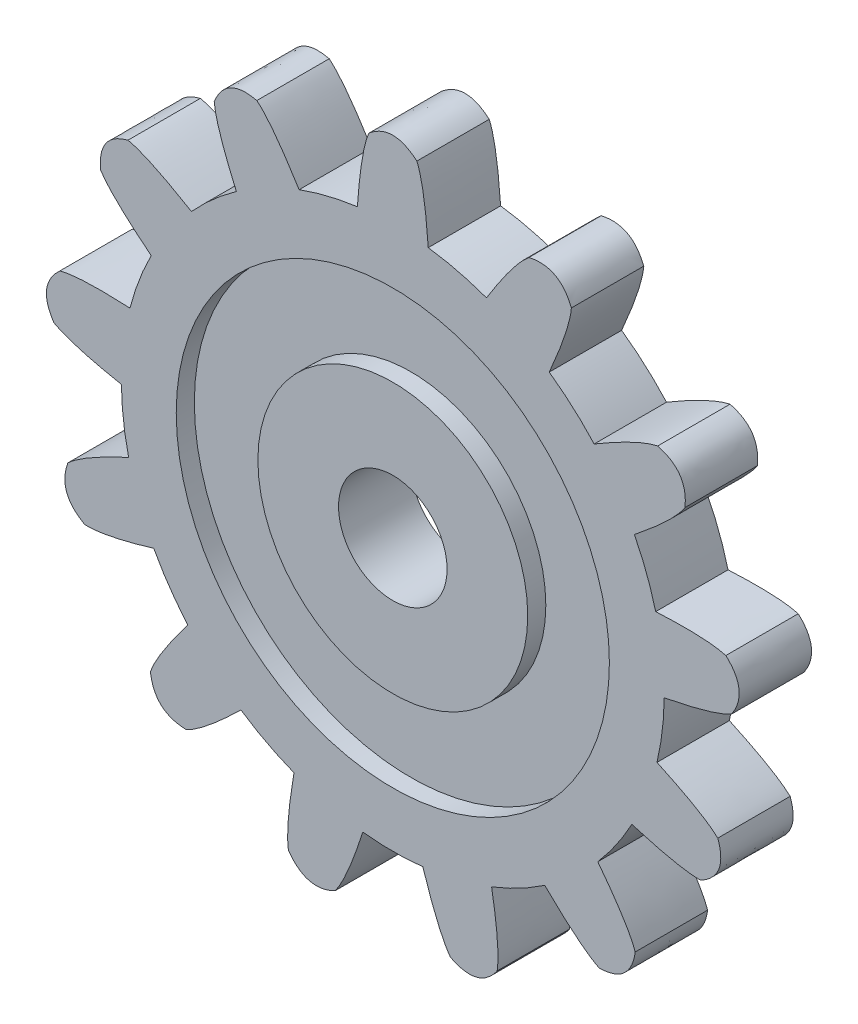
SolidWorks part; units mm, degrees
ref_plane "Front Plane" through (0, 0, 0) normal (0, 0, 1) x (1, 0, 0)
ref_plane "Top Plane" through (0, 0, 0) normal (0, 1, 0) x (1, 0, 0)
ref_plane "Right Plane" through (0, 0, 0) normal (1, 0, 0) x (0, 0, -1)
sketch "Sketch1" plane through (0, 0, 0) normal (0, 0, 1) x (1, 0, 0)
  line L0 (0, 39.9061) -> (0, 47.5043) construction
  line L1 (-3.3789, 47.5043) -> (3.3789, 47.5043) construction
  line L2 (-3.3789, 47.5043) -> (0, 50.4032) construction
  line L3 (0, 50.4032) -> (3.3789, 47.5043) construction
  line L4 (-4.4671, 44.9352) -> (4.4671, 44.9352) construction
  line L5 (4.4671, 44.9352) -> (4.4671, 44.9672) construction
  line L6 (-3.3789, 47.5043) -> (-4.4671, 44.9352) construction
  line L7 (-4.4671, 44.9352) -> (-4.973, 37.774) construction
  line L8 (0, 47.5043) -> (0, 48.9537) construction
  line L9 (-4.973, 37.774) -> (0, 0) construction
  line L10 (0, 0) -> (0, 39.9061) construction
  line L11 (3.3789, 47.5043) -> (4.4671, 44.9352) construction
  line L12 (4.4671, 44.9352) -> (4.973, 37.774) construction
  line L13 (19.0845, 43.6332) -> (23.4235, 44.6298) construction
  line L14 (23.4235, 44.6298) -> (25.0682, 40.4927) construction
  line L15 (19.0845, 43.6332) -> (16.927, 41.8641) construction
  line L16 (16.927, 41.8641) -> (13.1511, 35.7584) construction
  line L17 (25.0682, 40.4927) -> (24.8379, 37.7122) construction
  line L18 (24.8379, 37.7122) -> (21.9579, 31.1362) construction
  line L19 (37.1758, 29.7663) -> (41.481, 28.6323) construction
  line L20 (41.481, 28.6323) -> (41.0147, 24.2047) construction
  line L21 (37.1758, 29.7663) -> (34.4433, 29.2025) construction
  line L22 (34.4433, 29.2025) -> (28.2624, 25.5508) construction
  line L23 (41.0147, 24.2047) -> (39.5186, 21.8497) construction
  line L24 (39.5186, 21.8497) -> (33.9124, 17.3654) construction
  line L25 (46.7506, 9.0803) -> (50.0357, 6.0754) construction
  line L26 (50.0357, 6.0754) -> (47.5652, 2.3718) construction
  line L27 (46.7506, 9.0803) -> (44.0691, 9.8509) construction
  line L28 (44.0691, 9.8509) -> (36.8992, 9.4899) construction
  line L29 (47.5652, 2.3718) -> (45.146, 0.9818) construction
  line L30 (45.146, 0.9818) -> (38.0981, -0.3836) construction
  line L31 (45.6154, -13.6859) -> (47.1278, -17.8732) construction
  line L32 (47.1278, -17.8732) -> (43.2191, -20.0046) construction
  line L33 (45.6154, -13.6859) -> (43.5992, -11.7574) construction
  line L34 (43.5992, -11.7574) -> (37.0828, -8.745) construction
  line L35 (43.2191, -20.0046) -> (40.4311, -20.1111) construction
  line L36 (40.4311, -20.1111) -> (33.5559, -18.0447) construction
  line L37 (34.0303, -33.3168) -> (33.4235, -37.7273) construction
  line L38 (33.4235, -37.7273) -> (28.972, -37.7981) construction
  line L39 (34.0303, -33.3168) -> (33.1413, -30.6722) construction
  line L40 (33.1413, -30.6722) -> (28.7712, -24.9765) construction
  line L41 (28.972, -37.7981) -> (26.4539, -36.5967) construction
  line L42 (26.4539, -36.5967) -> (21.3264, -31.572) construction
  line L43 (14.6492, -45.3153) -> (12.0623, -48.9386) construction
  line L44 (12.0623, -48.9386) -> (8.0878, -46.9325) construction
  line L45 (14.6492, -45.3153) -> (15.091, -42.5604) construction
  line L46 (15.091, -42.5604) -> (13.8685, -35.4863) construction
  line L47 (8.0878, -46.9325) -> (6.4164, -44.6985) construction
  line L48 (6.4164, -44.6985) -> (4.2114, -37.8665) construction
  line L49 (-8.0878, -46.9325) -> (-12.0623, -48.9386) construction
  line L50 (-12.0623, -48.9386) -> (-14.6492, -45.3153) construction
  line L51 (-8.0878, -46.9325) -> (-6.4164, -44.6985) construction
  line L52 (-6.4164, -44.6985) -> (-4.2114, -37.8665) construction
  line L53 (-14.6492, -45.3153) -> (-15.091, -42.5604) construction
  line L54 (-15.091, -42.5604) -> (-13.8685, -35.4863) construction
  line L55 (-28.972, -37.7981) -> (-33.4235, -37.7273) construction
  line L56 (-33.4235, -37.7273) -> (-34.0303, -33.3168) construction
  line L57 (-28.972, -37.7981) -> (-26.4539, -36.5967) construction
  line L58 (-26.4539, -36.5967) -> (-21.3264, -31.572) construction
  line L59 (-34.0303, -33.3168) -> (-33.1413, -30.6722) construction
  line L60 (-33.1413, -30.6722) -> (-28.7712, -24.9765) construction
  line L61 (-43.2191, -20.0046) -> (-47.1278, -17.8732) construction
  line L62 (-47.1278, -17.8732) -> (-45.6154, -13.6859) construction
  line L63 (-43.2191, -20.0046) -> (-40.4311, -20.1111) construction
  line L64 (-40.4311, -20.1111) -> (-33.5559, -18.0447) construction
  line L65 (-45.6154, -13.6859) -> (-43.5992, -11.7574) construction
  line L66 (-43.5992, -11.7574) -> (-37.0828, -8.745) construction
  line L67 (-47.5652, 2.3718) -> (-50.0357, 6.0754) construction
  line L68 (-50.0357, 6.0754) -> (-46.7506, 9.0803) construction
  line L69 (-47.5652, 2.3718) -> (-45.146, 0.9818) construction
  line L70 (-45.146, 0.9818) -> (-38.0981, -0.3836) construction
  line L71 (-46.7506, 9.0803) -> (-44.0691, 9.8509) construction
  line L72 (-44.0691, 9.8509) -> (-36.8992, 9.4899) construction
  line L73 (-41.0147, 24.2047) -> (-41.481, 28.6323) construction
  line L74 (-41.481, 28.6323) -> (-37.1758, 29.7663) construction
  line L75 (-41.0147, 24.2047) -> (-39.5186, 21.8497) construction
  line L76 (-39.5186, 21.8497) -> (-33.9124, 17.3654) construction
  line L77 (-37.1758, 29.7663) -> (-34.4433, 29.2025) construction
  line L78 (-34.4433, 29.2025) -> (-28.2624, 25.5508) construction
  line L79 (-25.0682, 40.4927) -> (-23.4235, 44.6298) construction
  line L80 (-23.4235, 44.6298) -> (-19.0845, 43.6332) construction
  line L81 (-25.0682, 40.4927) -> (-24.8379, 37.7122) construction
  line L82 (-24.8379, 37.7122) -> (-21.9579, 31.1362) construction
  line L83 (-19.0845, 43.6332) -> (-16.927, 41.8641) construction
  line L84 (-16.927, 41.8641) -> (-13.1511, 35.7584) construction
  arc A0 (-4.973, 37.774) -> (-13.1511, 35.7584) centre (0, 0) ccw
  circle A1 centre (0, 0) radius 7.62
  arc A2 (-21.9579, 31.1362) -> (-28.2624, 25.5508) centre (0, 0) ccw
  arc A3 (13.1511, 35.7584) -> (4.973, 37.774) centre (0, 0) ccw
  arc A4 (28.2624, 25.5508) -> (21.9579, 31.1362) centre (0, 0) ccw
  arc A5 (36.8992, 9.4899) -> (33.9124, 17.3654) centre (0, 0) ccw
  arc A6 (-33.9124, 17.3654) -> (-36.8992, 9.4899) centre (0, 0) ccw
  arc A7 (-38.0981, -0.3836) -> (-37.0828, -8.745) centre (0, 0) ccw
  arc A8 (-33.5559, -18.0447) -> (-28.7712, -24.9765) centre (0, 0) ccw
  arc A9 (-21.3264, -31.572) -> (-13.8685, -35.4863) centre (0, 0) ccw
  arc A10 (-4.2114, -37.8665) -> (4.2114, -37.8665) centre (0, 0) ccw
  arc A11 (13.8685, -35.4863) -> (21.3264, -31.572) centre (0, 0) ccw
  arc A12 (28.7712, -24.9765) -> (33.5559, -18.0447) centre (0, 0) ccw
  arc A13 (37.0828, -8.745) -> (38.0981, -0.3836) centre (0, 0) ccw
  circle A14 centre (0, 0) radius 38.1 construction
  spline S0 degree 2 poles (-3.3789, 47.5043) (0, 50.4032) (3.3789, 47.5043) knots 0 0 0 1 1 1
  spline S1 degree 2 poles (-3.3789, 47.5043) (-4.4671, 44.9352) (-4.973, 37.774) knots 0 0 0 1 1 1
  spline S2 degree 2 poles (3.3789, 47.5043) (4.4671, 44.9352) (4.973, 37.774) knots 0 0 0 1 1 1
  spline S3 degree 2 poles (19.0845, 43.6332) (16.927, 41.8641) (13.1511, 35.7584) knots 0 0 0 1 1 1
  spline S4 degree 2 poles (19.0845, 43.6332) (23.4235, 44.6298) (25.0682, 40.4927) knots 0 0 0 1 1 1
  spline S5 degree 2 poles (25.0682, 40.4927) (24.8379, 37.7122) (21.9579, 31.1362) knots 0 0 0 1 1 1
  spline S6 degree 2 poles (37.1758, 29.7663) (34.4433, 29.2025) (28.2624, 25.5508) knots 0 0 0 1 1 1
  spline S7 degree 2 poles (37.1758, 29.7663) (41.481, 28.6323) (41.0147, 24.2047) knots 0 0 0 1 1 1
  spline S8 degree 2 poles (41.0147, 24.2047) (39.5186, 21.8497) (33.9124, 17.3654) knots 0 0 0 1 1 1
  spline S9 degree 2 poles (46.7506, 9.0803) (44.0691, 9.8509) (36.8992, 9.4899) knots 0 0 0 1 1 1
  spline S10 degree 2 poles (46.7506, 9.0803) (50.0357, 6.0754) (47.5652, 2.3718) knots 0 0 0 1 1 1
  spline S11 degree 2 poles (47.5652, 2.3718) (45.146, 0.9818) (38.0981, -0.3836) knots 0 0 0 1 1 1
  spline S12 degree 2 poles (45.6154, -13.6859) (43.5992, -11.7574) (37.0828, -8.745) knots 0 0 0 1 1 1
  spline S13 degree 2 poles (45.6154, -13.6859) (47.1278, -17.8732) (43.2191, -20.0046) knots 0 0 0 1 1 1
  spline S14 degree 2 poles (43.2191, -20.0046) (40.4311, -20.1111) (33.5559, -18.0447) knots 0 0 0 1 1 1
  spline S15 degree 2 poles (34.0303, -33.3168) (33.1413, -30.6722) (28.7712, -24.9765) knots 0 0 0 1 1 1
  spline S16 degree 2 poles (34.0303, -33.3168) (33.4235, -37.7273) (28.972, -37.7981) knots 0 0 0 1 1 1
  spline S17 degree 2 poles (28.972, -37.7981) (26.4539, -36.5967) (21.3264, -31.572) knots 0 0 0 1 1 1
  spline S18 degree 2 poles (14.6492, -45.3153) (15.091, -42.5604) (13.8685, -35.4863) knots 0 0 0 1 1 1
  spline S19 degree 2 poles (14.6492, -45.3153) (12.0623, -48.9386) (8.0878, -46.9325) knots 0 0 0 1 1 1
  spline S20 degree 2 poles (8.0878, -46.9325) (6.4164, -44.6985) (4.2114, -37.8665) knots 0 0 0 1 1 1
  spline S21 degree 2 poles (-8.0878, -46.9325) (-6.4164, -44.6985) (-4.2114, -37.8665) knots 0 0 0 1 1 1
  spline S22 degree 2 poles (-8.0878, -46.9325) (-12.0623, -48.9386) (-14.6492, -45.3153) knots 0 0 0 1 1 1
  spline S23 degree 2 poles (-14.6492, -45.3153) (-15.091, -42.5604) (-13.8685, -35.4863) knots 0 0 0 1 1 1
  spline S24 degree 2 poles (-28.972, -37.7981) (-26.4539, -36.5967) (-21.3264, -31.572) knots 0 0 0 1 1 1
  spline S25 degree 2 poles (-28.972, -37.7981) (-33.4235, -37.7273) (-34.0303, -33.3168) knots 0 0 0 1 1 1
  spline S26 degree 2 poles (-34.0303, -33.3168) (-33.1413, -30.6722) (-28.7712, -24.9765) knots 0 0 0 1 1 1
  spline S27 degree 2 poles (-43.2191, -20.0046) (-40.4311, -20.1111) (-33.5559, -18.0447) knots 0 0 0 1 1 1
  spline S28 degree 2 poles (-43.2191, -20.0046) (-47.1278, -17.8732) (-45.6154, -13.6859) knots 0 0 0 1 1 1
  spline S29 degree 2 poles (-45.6154, -13.6859) (-43.5992, -11.7574) (-37.0828, -8.745) knots 0 0 0 1 1 1
  spline S30 degree 2 poles (-47.5652, 2.3718) (-45.146, 0.9818) (-38.0981, -0.3836) knots 0 0 0 1 1 1
  spline S31 degree 2 poles (-47.5652, 2.3718) (-50.0357, 6.0754) (-46.7506, 9.0803) knots 0 0 0 1 1 1
  spline S32 degree 2 poles (-46.7506, 9.0803) (-44.0691, 9.8509) (-36.8992, 9.4899) knots 0 0 0 1 1 1
  spline S33 degree 2 poles (-41.0147, 24.2047) (-39.5186, 21.8497) (-33.9124, 17.3654) knots 0 0 0 1 1 1
  spline S34 degree 2 poles (-41.0147, 24.2047) (-41.481, 28.6323) (-37.1758, 29.7663) knots 0 0 0 1 1 1
  spline S35 degree 2 poles (-37.1758, 29.7663) (-34.4433, 29.2025) (-28.2624, 25.5508) knots 0 0 0 1 1 1
  spline S36 degree 2 poles (-25.0682, 40.4927) (-24.8379, 37.7122) (-21.9579, 31.1362) knots 0 0 0 1 1 1
  spline S37 degree 2 poles (-25.0682, 40.4927) (-23.4235, 44.6298) (-19.0845, 43.6332) knots 0 0 0 1 1 1
  spline S38 degree 2 poles (-19.0845, 43.6332) (-16.927, 41.8641) (-13.1511, 35.7584) knots 0 0 0 1 1 1
  point P8 (0, 47.5043)
  point P12 (0, 44.9352)
  point P106 (0, 0)
  dimension "D3" = 15.24
  dimension "D4" = 76.2
  dimension "D1" = 7.5
  dimension "D2" = 13
extrude "Boss-Extrude2" add sketch "Sketch1" along normal blind 10.16
sketch "Sketch2" plane through (0, 0, 0) normal (0, 0, -1) x (-1, 0, 0)
  circle A0 centre (0, 0) radius 19.05
  circle A1 centre (0, 0) radius 30.48
  dimension "D1" = 38.1
  dimension "D2" = 60.96
extrude "Cut-Extrude1" cut sketch "Sketch2" against normal blind 2.54
sketch "Sketch4" plane through (0, 0, 10.16) normal (0, 0, 1) x (1, 0, 0)
  circle A0 centre (0, 0) radius 30.4012
  circle A1 centre (0, 0) radius 18.94
extrude "Cut-Extrude3" cut sketch "Sketch4" against normal blind 2.54
